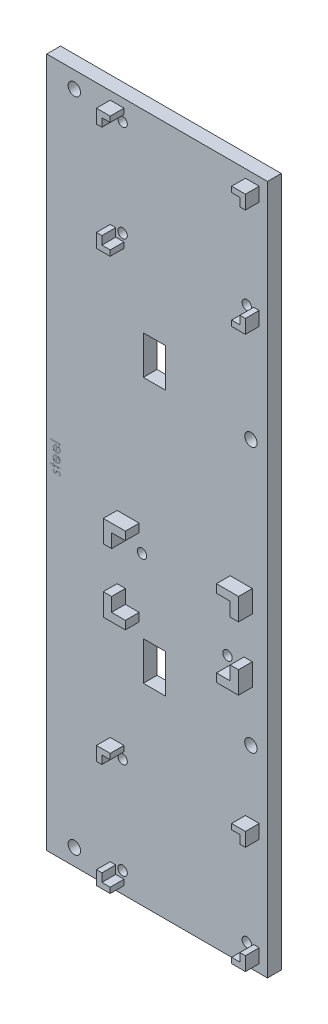
SolidWorks part; units mm, degrees
material "PLA"
ref_plane "정면" through (0, 0, 0) normal (0, 0, 1) x (1, 0, 0)
ref_plane "윗면" through (0, 0, 0) normal (0, 1, 0) x (1, 0, 0)
ref_plane "우측면" through (0, 0, 0) normal (1, 0, 0) x (0, 0, -1)
sketch "스케치1" plane through (0, 0, 0) normal (0, 0, 1) x (1, 0, 0)
  line L1 (-40, 125) -> (40, 125)
  line L2 (-40, 125) -> (-40, -125)
  line L3 (-40, -125) -> (40, -125)
  line L4 (40, 125) -> (40, -125)
  line L5 (-40, 125) -> (40, -125) construction
  line L6 (-40, -125) -> (40, 125) construction
  point P0 (0, 0)
  dimension "D1" = 80
  dimension "D2" = 250
extrude "보스-돌출1" add sketch "스케치1" along normal blind 5
sketch "스케치2" plane through (0, 0, 5) normal (0, 0, -1) x (-1, 0, 0)
  line L0 (35.1023, 125) -> (35.1023, -125) construction
  line L1 (-40, 125) -> (40, 125) construction
  line L2 (40, -125) -> (-40, -125) construction
  text T0 "steel\r\n"
extrude "temp" cut sketch "스케치2" along normal blind 0.01
sketch "스케치3" plane through (0, 0, 5) normal (0, 0, 1) x (1, 0, 0)
  line L0 (-12, -78) -> (-17, -78)
  line L1 (-17, -78) -> (-17, -83)
  line L2 (-17, -83) -> (-15, -83)
  line L3 (-15, -83) -> (-15, -80)
  line L4 (-15, -80) -> (-12, -80)
  line L5 (-12, -80) -> (-12, -78)
  line L6 (7.5, -100) -> (12.5, -100) construction
  line L7 (10, -97.5) -> (10, -102.5) construction
  line L8 (-40, -125) -> (40, -125) construction
  line L9 (40, -125) -> (40, 125) construction
  line L10 (32, -80) -> (32, -78)
  line L11 (35, -80) -> (32, -80)
  line L12 (35, -83) -> (35, -80)
  line L13 (37, -83) -> (35, -83)
  line L14 (37, -78) -> (37, -83)
  line L15 (32, -78) -> (37, -78)
  line L16 (32, -122) -> (37, -122)
  line L17 (37, -122) -> (37, -117)
  line L18 (37, -117) -> (35, -117)
  line L19 (35, -117) -> (35, -120)
  line L20 (35, -120) -> (32, -120)
  line L21 (32, -120) -> (32, -122)
  line L22 (-12, -120) -> (-12, -122)
  line L23 (-15, -120) -> (-12, -120)
  line L24 (-15, -117) -> (-15, -120)
  line L25 (-17, -117) -> (-15, -117)
  line L26 (-17, -122) -> (-17, -117)
  line L27 (-12, -122) -> (-17, -122)
  line L28 (-12, 0) -> (12, 0) construction
  line L29 (10, 97.5) -> (10, 102.5) construction
  line L30 (7.5, 100) -> (12.5, 100) construction
  line L31 (-12, 122) -> (-17, 122)
  line L32 (-17, 122) -> (-17, 117)
  line L33 (-17, 117) -> (-15, 117)
  line L34 (-15, 117) -> (-15, 120)
  line L35 (-15, 120) -> (-12, 120)
  line L36 (-12, 120) -> (-12, 122)
  line L37 (32, 120) -> (32, 122)
  line L38 (35, 120) -> (32, 120)
  line L39 (35, 117) -> (35, 120)
  line L40 (37, 117) -> (35, 117)
  line L41 (37, 122) -> (37, 117)
  line L42 (32, 122) -> (37, 122)
  line L43 (32, 78) -> (37, 78)
  line L44 (37, 78) -> (37, 83)
  line L45 (37, 83) -> (35, 83)
  line L46 (35, 83) -> (35, 80)
  line L47 (35, 80) -> (32, 80)
  line L48 (32, 80) -> (32, 78)
  line L49 (-12, 80) -> (-12, 78)
  line L50 (-15, 80) -> (-12, 80)
  line L51 (-15, 83) -> (-15, 80)
  line L52 (-17, 83) -> (-15, 83)
  line L53 (-17, 78) -> (-17, 83)
  line L54 (-12, 78) -> (-17, 78)
  point P2 (10, -100)
  point P64 (10, 100)
  dimension "D1" = 5
  dimension "D2" = 2
  dimension "D3" = 2
  dimension "D4" = 5
  dimension "D5" = 25
  dimension "D6" = 20
  dimension "D7" = 5
  dimension "D8" = 5
  dimension "D9" = 25
  dimension "D10" = 30
extrude "보스-돌출2" add sketch "스케치3" along normal blind 5
sketch "스케치4" plane through (0, 0, 5) normal (0, 0, 1) x (1, 0, 0)
  line L0 (-40, 125) -> (-40, -125) construction
  line L1 (-5, -41) -> (3, -41)
  line L2 (-5, -41) -> (-5, -55)
  line L3 (-5, -55) -> (3, -55)
  line L4 (3, -41) -> (3, -55)
  line L5 (-5, 55) -> (3, 55)
  line L6 (-5, 55) -> (-5, 41)
  line L7 (-5, 41) -> (3, 41)
  line L8 (3, 55) -> (3, 41)
  line L9 (-40, -125) -> (40, -125) construction
  line L10 (40, 125) -> (-40, 125) construction
  dimension "D1" = 14
  dimension "D2" = 14
  dimension "D3" = 8
  dimension "D4" = 8
  dimension "D5" = 35
  dimension "D6" = 35
  dimension "D7" = 70
  dimension "D8" = 70
extrude "컷-돌출1" cut sketch "스케치4" against normal blind 10
hole_wizard "M3 여유 구멍1" positions "스케치6" profile "스케치7" hole size "M3" standard "KS" end condition through all
sketch "스케치6" plane through (0, 0, 5) normal (0, 0, 1) x (1, 0, 0)
  line L0 (-15, 120) -> (-12, 120) construction
  line L1 (-15, 117) -> (-15, 120) construction
  line L2 (32, 120) -> (35, 120) construction
  line L3 (35, 120) -> (35, 117) construction
  line L4 (35, 83) -> (35, 80) construction
  line L5 (35, 80) -> (32, 80) construction
  line L6 (-12, 80) -> (-15, 80) construction
  line L7 (-15, 80) -> (-15, 83) construction
  line L8 (-15, -80) -> (-12, -80) construction
  line L9 (-15, -83) -> (-15, -80) construction
  line L10 (35, -80) -> (35, -83) construction
  line L11 (32, -80) -> (35, -80) construction
  line L12 (35, -120) -> (32, -120) construction
  line L13 (35, -117) -> (35, -120) construction
  line L14 (-12, -120) -> (-15, -120) construction
  line L15 (-15, -120) -> (-15, -117) construction
  point P0 (-12.5, 82.5)
  point P2 (32.5, 82.5)
  point P4 (32.5, 117.5)
  point P6 (-12.5, 117.5)
  point P8 (32.5, -82.5)
  point P10 (-12.5, -82.5)
  point P12 (-12.5, -117.5)
  point P14 (32.5, -117.5)
  dimension "D1" = 2.5
  dimension "D2" = 2.5
  dimension "D3" = 2.5
  dimension "D4" = 2.5
  dimension "D5" = 2.5
  dimension "D6" = 2.5
  dimension "D7" = 2.5
  dimension "D8" = 2.5
  dimension "D9" = 2.5
  dimension "D10" = 2.5
  dimension "D11" = 2.5
  dimension "D12" = 2.5
  dimension "D13" = 2.5
  dimension "D14" = 2.5
  dimension "D15" = 2.5
  dimension "D16" = 2.5
sketch "스케치7" plane through (-12.5, 82.5, 5) normal (1, 0, 0) x (0, -1, 0)
  line L0 (0, 0) -> (0, 5)
  line L1 (0, 5) -> (1.7, 5)
  line L2 (1.7, 5) -> (1.7, 0)
  line L5 (1.7, 0) -> (0, 0)
  line L11 (0, -6.35) -> (0, 107.95) construction
  dimension "관통 구멍 지름" = 3.4
  dimension "관통 구멍 깊이" = 5
sketch "스케치9" plane through (0, 0, 5) normal (0, 0, 1) x (1, 0, 0)
  line L0 (-14.5, -5.5) -> (-14.5, -13.5)
  line L1 (-14.5, -13.5) -> (-11.5, -13.5)
  line L2 (-11.5, -13.5) -> (-11.5, -8.5)
  line L3 (-11.5, -8.5) -> (-6.5, -8.5)
  line L4 (-6.5, -8.5) -> (-6.5, -5.5)
  line L5 (-6.5, -5.5) -> (-14.5, -5.5)
  line L6 (10, -13.5559) -> (10, -28.4441) construction
  line L7 (-7.8146, -21) -> (27.8146, -21) construction
  line L8 (40, -125) -> (40, 125) construction
  line L9 (3, -41) -> (-5, -41) construction
  line L10 (26.5, -5.5) -> (34.5, -5.5)
  line L11 (26.5, -8.5) -> (26.5, -5.5)
  line L12 (31.5, -8.5) -> (26.5, -8.5)
  line L13 (31.5, -13.5) -> (31.5, -8.5)
  line L14 (34.5, -13.5) -> (31.5, -13.5)
  line L15 (34.5, -5.5) -> (34.5, -13.5)
  line L16 (-14.5, -5.5) -> (-14.5, -13.5)
  line L17 (-14.5, -13.5) -> (-11.5, -13.5)
  line L18 (-11.5, -13.5) -> (-11.5, -8.5)
  line L19 (-11.5, -8.5) -> (-6.5, -8.5)
  line L20 (-6.5, -8.5) -> (-6.5, -5.5)
  line L21 (-6.5, -5.5) -> (-14.5, -5.5)
  line L22 (26.5, -5.5) -> (34.5, -5.5)
  line L23 (26.5, -8.5) -> (26.5, -5.5)
  line L24 (31.5, -8.5) -> (26.5, -8.5)
  line L25 (31.5, -13.5) -> (31.5, -8.5)
  line L26 (34.5, -13.5) -> (31.5, -13.5)
  line L27 (34.5, -5.5) -> (34.5, -13.5)
  line L28 (34.5, -36.5) -> (34.5, -28.5)
  line L29 (31.5, -28.5) -> (31.5, -33.5)
  line L30 (34.5, -36.5) -> (34.5, -28.5)
  line L31 (31.5, -28.5) -> (31.5, -33.5)
  line L32 (34.5, -28.5) -> (31.5, -28.5)
  line L33 (31.5, -33.5) -> (26.5, -33.5)
  line L34 (26.5, -33.5) -> (26.5, -36.5)
  line L35 (26.5, -36.5) -> (34.5, -36.5)
  line L36 (-6.5, -36.5) -> (-14.5, -36.5)
  line L37 (-6.5, -33.5) -> (-6.5, -36.5)
  line L38 (-11.5, -33.5) -> (-6.5, -33.5)
  line L39 (-11.5, -28.5) -> (-11.5, -33.5)
  line L40 (-14.5, -28.5) -> (-11.5, -28.5)
  line L41 (-14.5, -36.5) -> (-14.5, -28.5)
  line L42 (34.5, -28.5) -> (31.5, -28.5)
  line L43 (31.5, -33.5) -> (26.5, -33.5)
  line L44 (26.5, -33.5) -> (26.5, -36.5)
  line L45 (26.5, -36.5) -> (34.5, -36.5)
  line L46 (-6.5, -36.5) -> (-14.5, -36.5)
  line L47 (-6.5, -33.5) -> (-6.5, -36.5)
  line L48 (-11.5, -33.5) -> (-6.5, -33.5)
  line L49 (-11.5, -28.5) -> (-11.5, -33.5)
  line L50 (-14.5, -28.5) -> (-11.5, -28.5)
  line L51 (-14.5, -36.5) -> (-14.5, -28.5)
  point P10 (10, -21)
  dimension "D1" = 12.5
  dimension "D2" = 3
  dimension "D3" = 3
  dimension "D4" = 5
  dimension "D5" = 5
  dimension "D6" = 21.5
  dimension "D7" = 30
  dimension "D8" = 20
extrude "보스-돌출3" add sketch "스케치9" along normal blind 5 contours L41 L36 L37 L38 L39 L40 | L34 L35 L28 L32 L29 L33 | L15 L10 L11 L12 L13 L14 | L4 L5 L0 L1 L2 L3
hole_wizard "M3 여유 구멍2" positions "스케치13" profile "스케치12" hole size "M3" standard "KS" end condition through all
sketch "스케치13" plane through (0, 0, 5) normal (0, 0, 1) x (1, 0, 0)
  line L3 (-11.5, -33.5) -> (-6.5, -33.5) construction
  line L4 (-11.5, -13.5) -> (-11.5, -8.5) construction
  line L6 (-11.5, -8.5) -> (-6.5, -8.5) construction
  line L7 (31.5, -28.5) -> (31.5, -33.5) construction
  point P0 (-5.5, -14.5)
  point P7 (25.5, -31)
  dimension "D1" = 6
  dimension "D2" = 6
  dimension "D3" = 6
  dimension "D4" = 2.5
sketch "스케치12" plane through (-5.5, -14.5, 5) normal (1, 0, 0) x (0, -1, 0)
  line L0 (0, 0) -> (0, 5)
  line L1 (0, 5) -> (1.7, 5)
  line L2 (1.7, 5) -> (1.7, 0)
  line L5 (1.7, 0) -> (0, 0)
  line L11 (0, -6.35) -> (0, 107.95) construction
  dimension "관통 구멍 지름" = 3.4
  dimension "관통 구멍 깊이" = 5
hole_wizard "M4 여유 구멍1" positions "스케치14" profile "스케치15" hole size "M4" standard "KS" end condition through all
sketch "스케치14" plane through (0, 0, 5) normal (0, 0, 1) x (1, 0, 0)
  line L0 (40, 125) -> (-40, 125) construction
  line L1 (-40, 125) -> (-40, -125) construction
  line L2 (40, -125) -> (40, 125) construction
  line L3 (-5, 41) -> (3, 41) construction
  line L4 (-5, -55) -> (3, -55) construction
  line L5 (-40, -125) -> (40, -125) construction
  point P0 (-30, -119)
  point P2 (34, -55)
  point P4 (34, 41)
  point P6 (-30, 119)
  dimension "D1" = 6
  dimension "D2" = 10
  dimension "D3" = 6
  dimension "D4" = 0
  dimension "D5" = 0
  dimension "D6" = 6
  dimension "D7" = 10
  dimension "D8" = 6
sketch "스케치15" plane through (-30, -119, 5) normal (1, 0, 0) x (0, -1, 0)
  line L0 (0, 0) -> (0, 5)
  line L1 (0, 5) -> (2.25, 5)
  line L2 (2.25, 5) -> (2.25, 0)
  line L5 (2.25, 0) -> (0, 0)
  line L11 (0, -6.35) -> (0, 107.95) construction
  dimension "관통 구멍 지름" = 4.5
  dimension "관통 구멍 깊이" = 5
